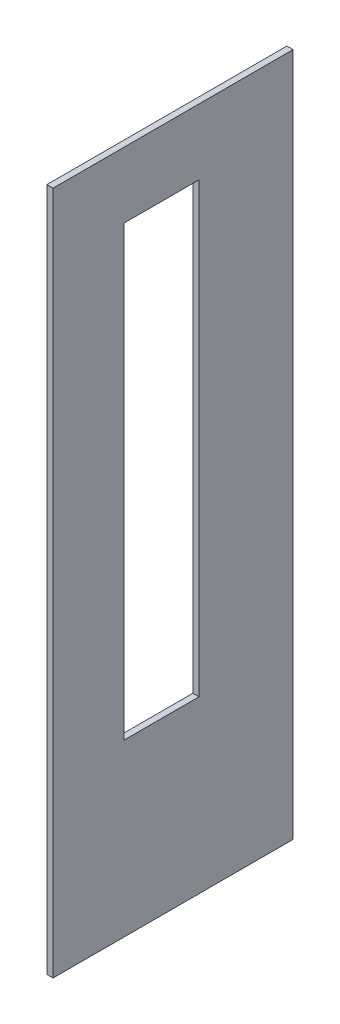
SolidWorks part; units mm, degrees
ref_plane "Спереди" through (0, 0, 0) normal (0, 0, 1) x (1, 0, 0)
ref_plane "Сверху" through (0, 0, 0) normal (0, 1, 0) x (1, 0, 0)
ref_plane "Справа" through (0, 0, 0) normal (1, 0, 0) x (0, 0, -1)
ref_plane "Плоскость4" through (0.5, 0, 0) normal (-1, 0, 0) x (0, -1, 0)
sketch "Эскиз1" plane through (0.5, 0, 0) normal (-1, 0, 0) x (0, -1, 0)
  line L0 (9.85, 42.25) -> (-100.85, 42.25)
  line L1 (-100.85, 42.25) -> (-100.85, 3.4)
  line L2 (-100.85, 3.4) -> (9.85, 3.4)
  line L3 (9.85, 3.4) -> (9.85, 42.25)
extrude "Бобышка-Вытянуть1" add sketch "Эскиз1" against normal blind 1
sketch "Эскиз2" plane through (0.5, 0, 0) normal (-1, 0, 0) x (0, 0, 1)
  line L0 (19.13, 89.71) -> (29.869, 89.71) construction
  line L1 (18.63, 90.21) -> (30.75, 90.21)
  line L2 (18.63, 90.21) -> (18.63, 17.75)
  line L3 (18.63, 17.75) -> (30.75, 17.75)
  line L4 (30.75, 90.21) -> (30.75, 17.75)
  line L5 (30.25, 66.271) -> (30.25, 89.329) construction
  line L6 (19.13, 89.71) -> (19.13, 65.89) construction
  line L7 (19.13, 18.25) -> (29.869, 18.25) construction
  dimension "D1" = 0.5
  dimension "D2" = 0.5
  dimension "D3" = 0.5
  dimension "D4" = 0.5
extrude "Вырез-Вытянуть1" cut sketch "Эскиз2" against normal blind 10 contours L2 L3 L4 L1
